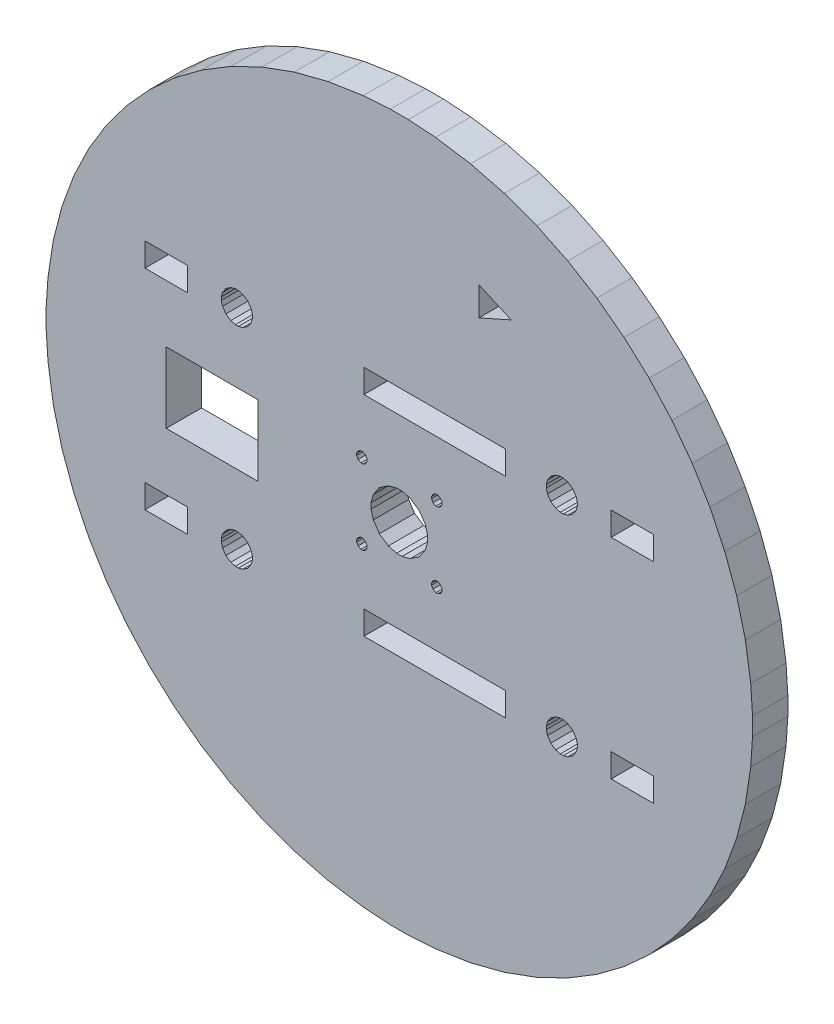
SolidWorks part; units mm, degrees
material "Balsa"
ref_plane "Front Plane" through (0, 0, 0) normal (0, 0, 1) x (1, 0, 0)
ref_plane "Top Plane" through (0, 0, 0) normal (0, 1, 0) x (1, 0, 0)
ref_plane "Right Plane" through (0, 0, 0) normal (1, 0, 0) x (0, 0, -1)
sketch "Sketch1" plane through (0, 0, 0) normal (0, 0, 1) x (1, 0, 0)
  line L0 (-32.9994, 5.0001) -> (-32.9994, -4.9963)
  line L1 (-20.0002, -4.9963) -> (-20.0002, 5.0001)
  line L2 (11.2466, 30.6716) -> (11.2466, 34.7562)
  line L3 (-32.9994, -4.9963) -> (-20.0002, -4.9963)
  line L4 (11.2466, 34.7562) -> (15.8257, 32.7153)
  line L5 (-20.0002, 5.0001) -> (-32.9994, 5.0001)
  line L6 (-16.9134, 32.7153) -> (15.8257, 32.7153)
  line L7 (15.8257, 32.7153) -> (11.2466, 30.6716)
  line L8 (50.0002, -0.0009) -> (50.0002, 1.278)
  line L9 (50.0002, 1.278) -> (49.7408, 5.1119)
  line L10 (49.7408, 5.1119) -> (48.9829, 10.0768)
  line L11 (48.9829, 10.0768) -> (47.751, 14.8683)
  line L12 (47.751, 14.8683) -> (46.0698, 19.4626)
  line L13 (46.0698, 19.4626) -> (43.9641, 23.8337)
  line L14 (43.9641, 23.8337) -> (41.4604, 27.9554)
  line L15 (41.4604, 27.9554) -> (38.5813, 31.8045)
  line L16 (38.5813, 31.8045) -> (35.354, 35.3557)
  line L17 (35.354, 35.3557) -> (31.8041, 38.5827)
  line L18 (31.8041, 38.5827) -> (27.954, 41.4618)
  line L19 (27.954, 41.4618) -> (23.8323, 43.9655)
  line L20 (23.8323, 43.9655) -> (19.4612, 46.0712)
  line L21 (19.4612, 46.0712) -> (14.8684, 47.7524)
  line L22 (14.8684, 47.7524) -> (10.0769, 48.9843)
  line L23 (10.0769, 48.9843) -> (5.1115, 49.7422)
  line L24 (5.1115, 49.7422) -> (1.2779, 50)
  line L25 (1.2779, 50) -> (0.0005, 50)
  line L26 (0.0005, 50) -> (-1.2784, 50)
  line L27 (-1.2784, 50) -> (-5.112, 49.7422)
  line L28 (-5.112, 49.7422) -> (-10.0769, 48.9843)
  line L29 (-10.0769, 48.9843) -> (-14.8684, 47.7524)
  line L30 (-14.8684, 47.7524) -> (-19.463, 46.0712)
  line L31 (-19.463, 46.0712) -> (-23.8338, 43.9655)
  line L32 (-23.8338, 43.9655) -> (-27.9557, 41.4618)
  line L33 (-27.9557, 41.4618) -> (-31.8046, 38.5827)
  line L34 (-31.8046, 38.5827) -> (-35.356, 35.3557)
  line L35 (-35.356, 35.3557) -> (-38.5831, 31.8045)
  line L36 (-38.5831, 31.8045) -> (-41.4619, 27.9554)
  line L37 (-41.4619, 27.9554) -> (-43.9659, 23.8337)
  line L38 (-43.9659, 23.8337) -> (-46.0715, 19.4626)
  line L39 (-46.0715, 19.4626) -> (-47.7525, 14.8683)
  line L40 (-47.7525, 14.8683) -> (-48.9844, 10.0768)
  line L41 (-48.9844, 10.0768) -> (-49.7426, 5.1119)
  line L42 (-49.7426, 5.1119) -> (-50.0002, 1.278)
  line L43 (-50.0002, 1.278) -> (-50.0002, -0.0009)
  line L44 (-50.0002, -0.0009) -> (-50.0002, -1.2783)
  line L45 (-50.0002, -1.2783) -> (-49.7426, -5.1119)
  line L46 (-49.7426, -5.1119) -> (-48.9844, -10.0771)
  line L47 (-48.9844, -10.0771) -> (-47.7525, -14.8683)
  line L48 (-47.7525, -14.8683) -> (-46.0715, -19.4616)
  line L49 (-46.0715, -19.4616) -> (-43.9659, -23.8324)
  line L50 (-43.9659, -23.8324) -> (-41.4619, -27.9544)
  line L51 (-41.4619, -27.9544) -> (-38.5831, -31.8045)
  line L52 (-38.5831, -31.8045) -> (-35.356, -35.3541)
  line L53 (-35.356, -35.3541) -> (-31.8046, -38.5817)
  line L54 (-31.8046, -38.5817) -> (-27.9557, -41.4603)
  line L55 (-27.9557, -41.4603) -> (-23.8338, -43.9645)
  line L56 (-23.8338, -43.9645) -> (-19.463, -46.0699)
  line L57 (-19.463, -46.0699) -> (-14.8684, -47.7511)
  line L58 (-14.8684, -47.7511) -> (-10.0769, -48.983)
  line L59 (-10.0769, -48.983) -> (-5.112, -49.7412)
  line L60 (-5.112, -49.7412) -> (-1.2784, -50)
  line L61 (-1.2784, -50) -> (0.0005, -50)
  line L62 (0.0005, -50) -> (1.2779, -50)
  line L63 (1.2779, -50) -> (5.1115, -49.7412)
  line L64 (5.1115, -49.7412) -> (10.0769, -48.983)
  line L65 (10.0769, -48.983) -> (14.8684, -47.7511)
  line L66 (14.8684, -47.7511) -> (19.4612, -46.0699)
  line L67 (19.4612, -46.0699) -> (23.8323, -43.9645)
  line L68 (23.8323, -43.9645) -> (27.954, -41.4603)
  line L69 (27.954, -41.4603) -> (31.8041, -38.5817)
  line L70 (31.8041, -38.5817) -> (35.354, -35.3557)
  line L71 (35.354, -35.3557) -> (38.5813, -31.8045)
  line L72 (38.5813, -31.8045) -> (41.4604, -27.9556)
  line L73 (41.4604, -27.9556) -> (43.9641, -23.8324)
  line L74 (43.9641, -23.8324) -> (46.0698, -19.4629)
  line L75 (46.0698, -19.4629) -> (47.751, -14.8683)
  line L76 (47.751, -14.8683) -> (48.9829, -10.0771)
  line L77 (48.9829, -10.0771) -> (49.7408, -5.1119)
  line L78 (49.7408, -5.1119) -> (50.0002, -1.2783)
  line L79 (50.0002, -1.2783) -> (50.0002, -0.0009)
  line L80 (4.001, -0.0009) -> (4.001, 0.3893)
  line L81 (4.001, 0.3893) -> (3.6853, 1.5561)
  line L82 (3.6853, 1.5561) -> (2.8283, 2.8284)
  line L83 (2.8283, 2.8284) -> (1.5563, 3.6857)
  line L84 (1.5563, 3.6857) -> (0.3894, 3.9996)
  line L85 (0.3894, 3.9996) -> (0.0005, 3.9996)
  line L86 (0.0005, 3.9996) -> (-0.3894, 3.9996)
  line L87 (-0.3894, 3.9996) -> (-1.5568, 3.6857)
  line L88 (-1.5568, 3.6857) -> (-2.8285, 2.8284)
  line L89 (-2.8285, 2.8284) -> (-3.6858, 1.5561)
  line L90 (-3.6858, 1.5561) -> (-4, 0.3893)
  line L91 (-4, 0.3893) -> (-4, -0.0009)
  line L92 (-4, -0.0009) -> (-4, -0.3893)
  line L93 (-4, -0.3893) -> (-3.6858, -1.5566)
  line L94 (-3.6858, -1.5566) -> (-2.8285, -2.8284)
  line L95 (-2.8285, -2.8284) -> (-1.5568, -3.6841)
  line L96 (-1.5568, -3.6841) -> (-0.3894, -4.0001)
  line L97 (-0.3894, -4.0001) -> (0.0005, -4.0001)
  line L98 (0.0005, -4.0001) -> (0.3894, -4.0001)
  line L99 (0.3894, -4.0001) -> (1.5563, -3.6841)
  line L100 (1.5563, -3.6841) -> (2.8283, -2.8284)
  line L101 (2.8283, -2.8284) -> (3.6853, -1.5566)
  line L102 (3.6853, -1.5566) -> (4.001, -0.3893)
  line L103 (4.001, -0.3893) -> (4.001, -0.0009)
  line L104 (-20.7996, 14.8157) -> (-20.7996, 15.0308)
  line L105 (-20.7996, 15.0308) -> (-20.9733, 15.6729)
  line L106 (-20.9733, 15.6729) -> (-21.4445, 16.373)
  line L107 (-21.4445, 16.373) -> (-22.1445, 16.8441)
  line L108 (-22.1445, 16.8441) -> (-22.7868, 17.0166)
  line L109 (-22.7868, 17.0166) -> (-23.0002, 17.0166)
  line L110 (-23.0002, 17.0166) -> (-23.2151, 17.0166)
  line L111 (-23.2151, 17.0166) -> (-23.8575, 16.8441)
  line L112 (-23.8575, 16.8441) -> (-24.556, 16.373)
  line L113 (-24.556, 16.373) -> (-25.0274, 15.6729)
  line L114 (-25.0274, 15.6729) -> (-25.1996, 15.0308)
  line L115 (-25.1996, 15.0308) -> (-25.1996, 14.8157)
  line L116 (-25.1996, 14.8157) -> (-25.1996, 14.6023)
  line L117 (-25.1996, 14.6023) -> (-25.0274, 13.9602)
  line L118 (-25.0274, 13.9602) -> (-24.556, 13.2615)
  line L119 (-24.556, 13.2615) -> (-23.8575, 12.79)
  line L120 (-23.8575, 12.79) -> (-23.2151, 12.6166)
  line L121 (-23.2151, 12.6166) -> (-23.0002, 12.6166)
  line L122 (-23.0002, 12.6166) -> (-22.7868, 12.6166)
  line L123 (-22.7868, 12.6166) -> (-22.1445, 12.79)
  line L124 (-22.1445, 12.79) -> (-21.4445, 13.2615)
  line L125 (-21.4445, 13.2615) -> (-20.9733, 13.9602)
  line L126 (-20.9733, 13.9602) -> (-20.7996, 14.6023)
  line L127 (-20.7996, 14.6023) -> (-20.7996, 14.8157)
  line L128 (-20.7996, -14.8119) -> (-20.7996, -14.597)
  line L129 (-20.7996, -14.597) -> (-20.9733, -13.9546)
  line L130 (-20.9733, -13.9546) -> (-21.4445, -13.2561)
  line L131 (-21.4445, -13.2561) -> (-22.1445, -12.785)
  line L132 (-22.1445, -12.785) -> (-22.7868, -12.6128)
  line L133 (-22.7868, -12.6128) -> (-23.0002, -12.6128)
  line L134 (-23.0002, -12.6128) -> (-23.2151, -12.6128)
  line L135 (-23.2151, -12.6128) -> (-23.8575, -12.785)
  line L136 (-23.8575, -12.785) -> (-24.556, -13.2561)
  line L137 (-24.556, -13.2561) -> (-25.0274, -13.9546)
  line L138 (-25.0274, -13.9546) -> (-25.1996, -14.597)
  line L139 (-25.1996, -14.597) -> (-25.1996, -14.8119)
  line L140 (-25.1996, -14.8119) -> (-25.1996, -15.0255)
  line L141 (-25.1996, -15.0255) -> (-25.0274, -15.6679)
  line L142 (-25.0274, -15.6679) -> (-24.556, -16.3664)
  line L143 (-24.556, -16.3664) -> (-23.8575, -16.8375)
  line L144 (-23.8575, -16.8375) -> (-23.2151, -17.0113)
  line L145 (-23.2151, -17.0113) -> (-23.0002, -17.0113)
  line L146 (-23.0002, -17.0113) -> (-22.7868, -17.0113)
  line L147 (-22.7868, -17.0113) -> (-22.1445, -16.8375)
  line L148 (-22.1445, -16.8375) -> (-21.4445, -16.3664)
  line L149 (-21.4445, -16.3664) -> (-20.9733, -15.6679)
  line L150 (-20.9733, -15.6679) -> (-20.7996, -15.0255)
  line L151 (-20.7996, -15.0255) -> (-20.7996, -14.8119)
  line L152 (25.2009, 14.8157) -> (25.2009, 15.0308)
  line L153 (25.2009, 15.0308) -> (25.0271, 15.6729)
  line L154 (25.0271, 15.6729) -> (24.556, 16.373)
  line L155 (24.556, 16.373) -> (23.8557, 16.8441)
  line L156 (23.8557, 16.8441) -> (23.2136, 17.0166)
  line L157 (23.2136, 17.0166) -> (23, 17.0166)
  line L158 (23, 17.0166) -> (22.7851, 17.0166)
  line L159 (22.7851, 17.0166) -> (22.143, 16.8441)
  line L160 (22.143, 16.8441) -> (21.4442, 16.373)
  line L161 (21.4442, 16.373) -> (20.9728, 15.6729)
  line L162 (20.9728, 15.6729) -> (20.8006, 15.0308)
  line L163 (20.8006, 15.0308) -> (20.8006, 14.8157)
  line L164 (20.8006, 14.8157) -> (20.8006, 14.6023)
  line L165 (20.8006, 14.6023) -> (20.9728, 13.9602)
  line L166 (20.9728, 13.9602) -> (21.4442, 13.2615)
  line L167 (21.4442, 13.2615) -> (22.143, 12.79)
  line L168 (22.143, 12.79) -> (22.7851, 12.6166)
  line L169 (22.7851, 12.6166) -> (23, 12.6166)
  line L170 (23, 12.6166) -> (23.2136, 12.6166)
  line L171 (23.2136, 12.6166) -> (23.8557, 12.79)
  line L172 (23.8557, 12.79) -> (24.556, 13.2615)
  line L173 (24.556, 13.2615) -> (25.0271, 13.9602)
  line L174 (25.0271, 13.9602) -> (25.2009, 14.6023)
  line L175 (25.2009, 14.6023) -> (25.2009, 14.8157)
  line L176 (25.2009, -14.8119) -> (25.2009, -14.597)
  line L177 (25.2009, -14.597) -> (25.0271, -13.9546)
  line L178 (25.0271, -13.9546) -> (24.556, -13.2561)
  line L179 (24.556, -13.2561) -> (23.8557, -12.785)
  line L180 (23.8557, -12.785) -> (23.2136, -12.6128)
  line L181 (23.2136, -12.6128) -> (23, -12.6128)
  line L182 (23, -12.6128) -> (22.7851, -12.6128)
  line L183 (22.7851, -12.6128) -> (22.143, -12.785)
  line L184 (22.143, -12.785) -> (21.4442, -13.2561)
  line L185 (21.4442, -13.2561) -> (20.9728, -13.9546)
  line L186 (20.9728, -13.9546) -> (20.8006, -14.597)
  line L187 (20.8006, -14.597) -> (20.8006, -14.8119)
  line L188 (20.8006, -14.8119) -> (20.8006, -15.0255)
  line L189 (20.8006, -15.0255) -> (20.9728, -15.6679)
  line L190 (20.9728, -15.6679) -> (21.4442, -16.3664)
  line L191 (21.4442, -16.3664) -> (22.143, -16.8375)
  line L192 (22.143, -16.8375) -> (22.7851, -17.0113)
  line L193 (22.7851, -17.0113) -> (23, -17.0113)
  line L194 (23, -17.0113) -> (23.2136, -17.0113)
  line L195 (23.2136, -17.0113) -> (23.8557, -16.8375)
  line L196 (23.8557, -16.8375) -> (24.556, -16.3664)
  line L197 (24.556, -16.3664) -> (25.0271, -15.6679)
  line L198 (25.0271, -15.6679) -> (25.2009, -15.0255)
  line L199 (25.2009, -15.0255) -> (25.2009, -14.8119)
  line L200 (6.0541, 5.3059) -> (6.0541, 5.4395)
  line L201 (6.0541, 5.4395) -> (5.8336, 5.8365)
  line L202 (5.8336, 5.8365) -> (5.4353, 6.0555)
  line L203 (5.4353, 6.0555) -> (5.303, 6.0555)
  line L204 (5.303, 6.0555) -> (5.1694, 6.0555)
  line L205 (5.1694, 6.0555) -> (4.7724, 5.8365)
  line L206 (4.7724, 5.8365) -> (4.5535, 5.4395)
  line L207 (4.5535, 5.4395) -> (4.5535, 5.3059)
  line L208 (4.5535, 5.3059) -> (4.5535, 5.1736)
  line L209 (4.5535, 5.1736) -> (4.7724, 4.7753)
  line L210 (4.7724, 4.7753) -> (5.1694, 4.5564)
  line L211 (5.1694, 4.5564) -> (5.303, 4.5564)
  line L212 (5.303, 4.5564) -> (5.4353, 4.5564)
  line L213 (5.4353, 4.5564) -> (5.8336, 4.7753)
  line L214 (5.8336, 4.7753) -> (6.0541, 5.1736)
  line L215 (6.0541, 5.1736) -> (6.0541, 5.3059)
  line L216 (6.0541, -5.3021) -> (6.0541, -5.1685)
  line L217 (6.0541, -5.1685) -> (5.8336, -4.7702)
  line L218 (5.8336, -4.7702) -> (5.4353, -4.551)
  line L219 (5.4353, -4.551) -> (5.303, -4.551)
  line L220 (5.303, -4.551) -> (5.1694, -4.551)
  line L221 (5.1694, -4.551) -> (4.7724, -4.7702)
  line L222 (4.7724, -4.7702) -> (4.5535, -5.1685)
  line L223 (4.5535, -5.1685) -> (4.5535, -5.3021)
  line L224 (4.5535, -5.3021) -> (4.5535, -5.4345)
  line L225 (4.5535, -5.4345) -> (4.7724, -5.8312)
  line L226 (4.7724, -5.8312) -> (5.1694, -6.0517)
  line L227 (5.1694, -6.0517) -> (5.303, -6.0517)
  line L228 (5.303, -6.0517) -> (5.4353, -6.0517)
  line L229 (5.4353, -6.0517) -> (5.8336, -5.8312)
  line L230 (5.8336, -5.8312) -> (6.0541, -5.4345)
  line L231 (6.0541, -5.4345) -> (6.0541, -5.3021)
  line L232 (-4.5524, -5.3021) -> (-4.5524, -5.1685)
  line L233 (-4.5524, -5.1685) -> (-4.7729, -4.7702)
  line L234 (-4.7729, -4.7702) -> (-5.1712, -4.551)
  line L235 (-5.1712, -4.551) -> (-5.3035, -4.551)
  line L236 (-5.3035, -4.551) -> (-5.4371, -4.551)
  line L237 (-5.4371, -4.551) -> (-5.8341, -4.7702)
  line L238 (-5.8341, -4.7702) -> (-6.0531, -5.1685)
  line L239 (-6.0531, -5.1685) -> (-6.0531, -5.3021)
  line L240 (-6.0531, -5.3021) -> (-6.0531, -5.4345)
  line L241 (-6.0531, -5.4345) -> (-5.8341, -5.8312)
  line L242 (-5.8341, -5.8312) -> (-5.4371, -6.0517)
  line L243 (-5.4371, -6.0517) -> (-5.3035, -6.0517)
  line L244 (-5.3035, -6.0517) -> (-5.1712, -6.0517)
  line L245 (-5.1712, -6.0517) -> (-4.7729, -5.8312)
  line L246 (-4.7729, -5.8312) -> (-4.5524, -5.4345)
  line L247 (-4.5524, -5.4345) -> (-4.5524, -5.3021)
  line L248 (-4.5524, 5.3059) -> (-4.5524, 5.4395)
  line L249 (-4.5524, 5.4395) -> (-4.7729, 5.8365)
  line L250 (-4.7729, 5.8365) -> (-5.1712, 6.0555)
  line L251 (-5.1712, 6.0555) -> (-5.3035, 6.0555)
  line L252 (-5.3035, 6.0555) -> (-5.4371, 6.0555)
  line L253 (-5.4371, 6.0555) -> (-5.8341, 5.8365)
  line L254 (-5.8341, 5.8365) -> (-6.0531, 5.4395)
  line L255 (-6.0531, 5.4395) -> (-6.0531, 5.3059)
  line L256 (-6.0531, 5.3059) -> (-6.0531, 5.1736)
  line L257 (-6.0531, 5.1736) -> (-5.8341, 4.7753)
  line L258 (-5.8341, 4.7753) -> (-5.4371, 4.5564)
  line L259 (-5.4371, 4.5564) -> (-5.3035, 4.5564)
  line L260 (-5.3035, 4.5564) -> (-5.1712, 4.5564)
  line L261 (-5.1712, 4.5564) -> (-4.7729, 4.7753)
  line L262 (-4.7729, 4.7753) -> (-4.5524, 5.1736)
  line L263 (-4.5524, 5.1736) -> (-4.5524, 5.3059)
  line L264 (-36.0131, 16.489) -> (-29.987, 16.489)
  line L265 (-29.987, 16.489) -> (-29.987, 13.1385)
  line L266 (-29.987, 13.1385) -> (-36.0131, 13.1385)
  line L267 (-36.0131, 13.1385) -> (-36.0131, 16.489)
  line L268 (29.9865, 16.489) -> (36.0129, 16.489)
  line L269 (36.0129, 16.489) -> (36.0129, 13.1385)
  line L270 (36.0129, 13.1385) -> (29.9865, 13.1385)
  line L271 (29.9865, 13.1385) -> (29.9865, 16.489)
  line L272 (-5.0129, 16.489) -> (15.0129, 16.489)
  line L273 (15.0129, 16.489) -> (15.0129, 13.1385)
  line L274 (15.0129, 13.1385) -> (-5.0129, 13.1385)
  line L275 (-5.0129, 13.1385) -> (-5.0129, 16.489)
  line L276 (-36.0131, -13.1347) -> (-29.987, -13.1347)
  line L277 (-29.987, -13.1347) -> (-29.987, -16.4847)
  line L278 (-29.987, -16.4847) -> (-36.0131, -16.4847)
  line L279 (-36.0131, -16.4847) -> (-36.0131, -13.1347)
  line L280 (29.9865, -13.1347) -> (36.0129, -13.1347)
  line L281 (36.0129, -13.1347) -> (36.0129, -16.4847)
  line L282 (36.0129, -16.4847) -> (29.9865, -16.4847)
  line L283 (29.9865, -16.4847) -> (29.9865, -13.1347)
  line L284 (-5.0129, -13.1347) -> (15.0129, -13.1347)
  line L285 (15.0129, -13.1347) -> (15.0129, -16.4847)
  line L286 (15.0129, -16.4847) -> (-5.0129, -16.4847)
  line L287 (-5.0129, -16.4847) -> (-5.0129, -13.1347)
extrude "Boss-Extrude1" add sketch "Sketch1" along normal blind 5 contours L78 L79 L8 L9 L10 L11 L12 L13 L14 L15 L16 L17 L18 L19 L20 L21 L22 L23 L24 L25 L26 L27 L28 L29 L30 L31 L32 L33 L34 L35 L36 L37 L38 L39 L40 L41 L42 L43 L44 L45 L46 L47 L48 L49 L50 L51 L52 L53 L54 L55 L56
